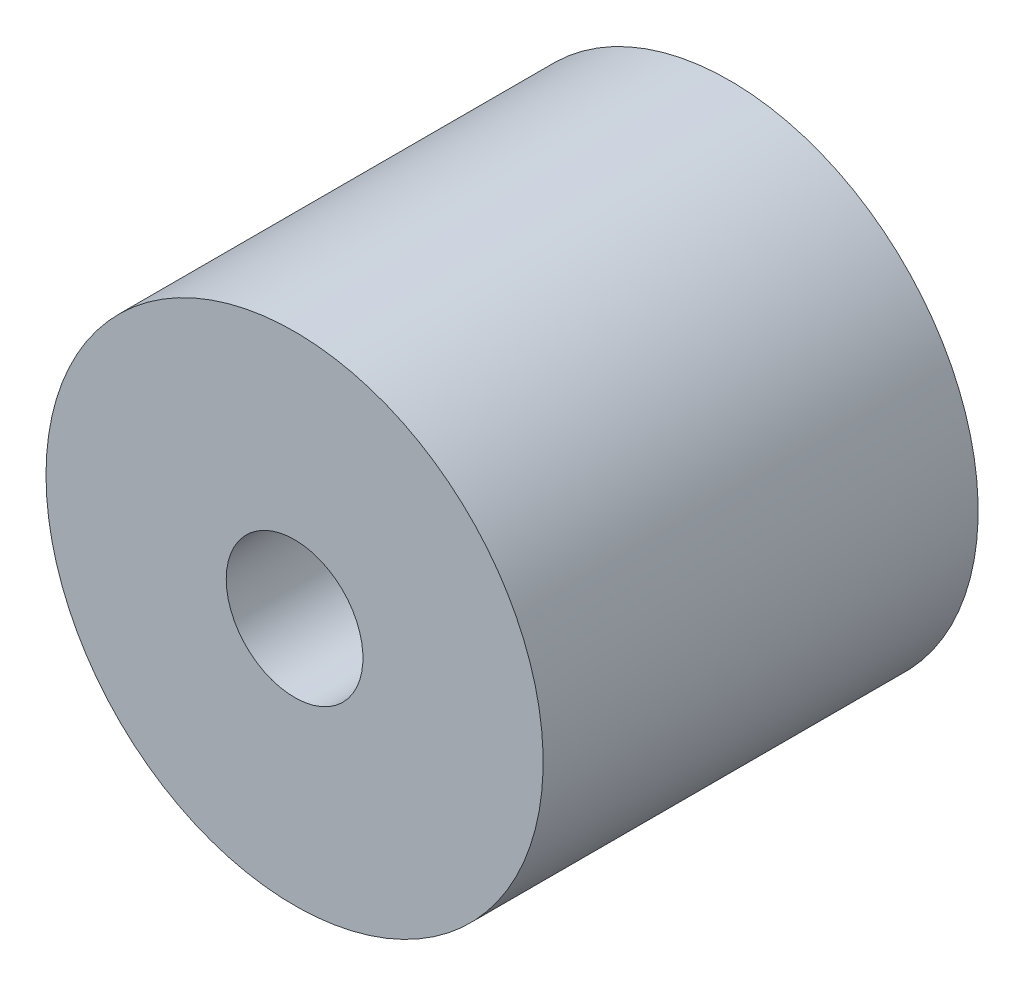
SolidWorks part; units mm, degrees
ref_plane "前视基准面" through (0, 0, 0) normal (0, 0, 1) x (1, 0, 0)
ref_plane "上视基准面" through (0, 0, 0) normal (0, 1, 0) x (1, 0, 0)
ref_plane "右视基准面" through (0, 0, 0) normal (1, 0, 0) x (0, 0, -1)
other "Configuration Table"
sketch "草图1" plane through (0, 0, 0) normal (0, 0, 1) x (1, 0, 0)
  circle A0 centre (0, 0) radius 1.65
  circle A1 centre (0, 0) radius 6
  dimension "D1" = 3.3
  dimension "D2" = 12
extrude "凸台-拉伸1" add sketch "草图1" along normal blind 10.5
